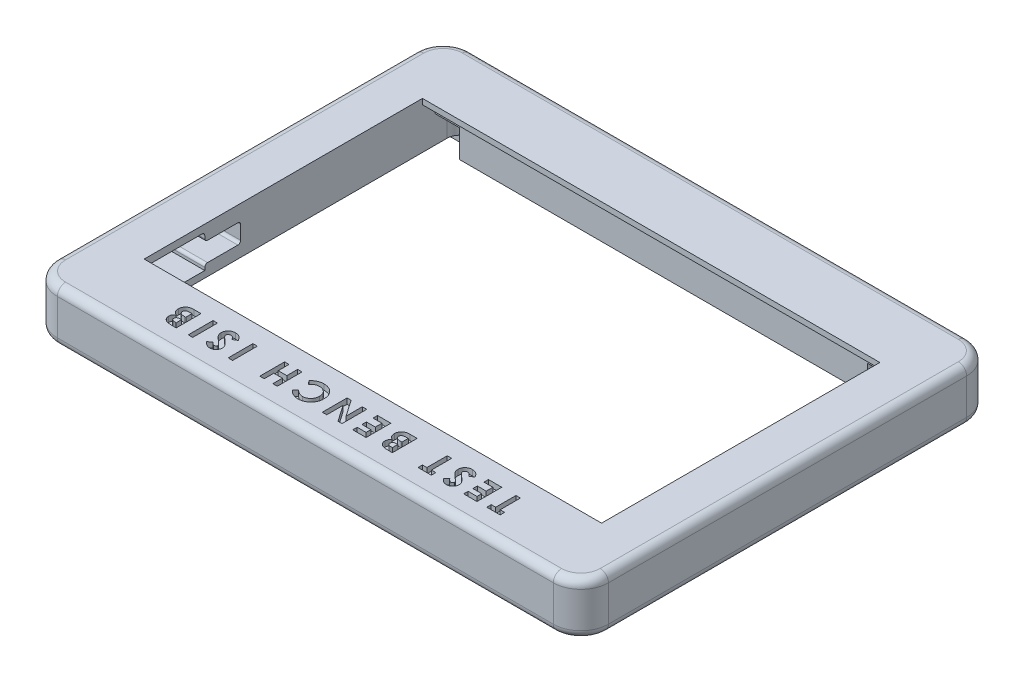
SolidWorks part; units mm, degrees
ref_plane "Plan de face" through (0, 0, 0) normal (0, 0, 1) x (1, 0, 0)
ref_plane "Plan de dessus" through (0, 0, 0) normal (0, 1, 0) x (1, 0, 0)
ref_plane "Plan de droite" through (0, 0, 0) normal (1, 0, 0) x (0, 0, -1)
sketch "Esquisse1" plane through (0, 0, 0) normal (0, 1, 0) x (1, 0, 0)
  line L0 (-100, -75) -> (100, 75) construction
  line L1 (-90, 75) -> (90, 75)
  line L2 (-100, 65) -> (-100, -65)
  line L3 (-90, -75) -> (90, -75)
  line L4 (100, 65) -> (100, -65)
  arc A0 (90, 75) -> (100, 65) centre (90, 65) cw
  arc A1 (90, -75) -> (100, -65) centre (90, -65) ccw
  arc A2 (-90, -75) -> (-100, -65) centre (-90, -65) cw
  arc A3 (-90, 75) -> (-100, 65) centre (-90, 65) ccw
  point P15 (-100, 75)
  dimension "D3" = 10
  dimension "D1" = 200
  dimension "D2" = 150
extrude "Boss.-Extru.1" add sketch "Esquisse1" along normal blind 19
sketch "Esquisse3" plane through (0, 0, 0) normal (0, -1, 0) x (1, 0, 0)
  line L0 (85.1, 62.5) -> (-85.1, -62.5) construction
  line L1 (85.1, -62.5) -> (-85.1, -62.5)
  line L2 (85.1, -62.5) -> (85.1, 62.5)
  line L3 (85.1, 62.5) -> (-85.1, 62.5)
  line L4 (-85.1, -62.5) -> (-85.1, 62.5)
  dimension "D1" = 170.2
  dimension "125" = 125
extrude "Enlèv. mat.-Extru.2" cut sketch "Esquisse3" against normal blind 2
sketch "Esquisse2" plane through (0, 19, 0) normal (0, 1, 0) x (1, 0, 0)
  line L0 (-83, -50.5) -> (83, 50.5) construction
  line L1 (-83, 50.5) -> (83, 50.5)
  line L2 (-83, 50.5) -> (-83, -50.5)
  line L3 (-83, -50.5) -> (83, -50.5)
  line L4 (83, 50.5) -> (83, -50.5)
  dimension "D1" = 166
  dimension "D2" = 101
extrude "Enlèv. mat.-Extru.1" cut sketch "Esquisse2" against normal up to surface (17 mm away) up to face at (0, 2, 0)
sketch "Esquisse4" plane through (0, 2, 0) normal (0, -1, 0) x (1, 0, 0)
  line L0 (-83, 50.5) -> (83, 50.5) construction
  line L6 (-83, -55) -> (-83, -59.5)
  line L17 (-83, -50.5) -> (-83, 50.5) construction
  line L18 (-74, 52.5) -> (74, 52.5)
  line L19 (-83, 52.5) -> (-83, -55)
  line L20 (-74, -55) -> (74, -55)
  line L21 (83, 52.5) -> (83, -55)
  line L22 (-74, -59.5) -> (-74, -55)
  line L23 (83, -55) -> (83, -59.5)
  line L25 (74, -59.5) -> (74, -55)
  line L26 (83, 52.5) -> (83, 57)
  line L28 (74, 57) -> (74, 52.5)
  line L29 (-83, 52.5) -> (-83, 57)
  line L31 (-74, 57) -> (-74, 52.5)
  line L32 (83, 50.5) -> (83, -50.5) construction
  arc A0 (-83, 57) -> (-74, 57) centre (-78.5, 57) cw
  arc A1 (74, 57) -> (83, 57) centre (78.5, 57) cw
  arc A2 (-83, -59.5) -> (-74, -59.5) centre (-78.5, -59.5) ccw
  arc A3 (74, -59.5) -> (83, -59.5) centre (78.5, -59.5) ccw
  dimension "D1" = 2
  dimension "D4" = 4.5
  dimension "D2" = 107.5
  dimension "D3" = 4.5
extrude "Enlèv. mat.-Extru.3" cut sketch "Esquisse4" against normal offset from surface (10 mm away) 7 up to face at (0, 19, 0)
hole_wizard "Trou taraudé M3x0.51" positions "Esquisse5" profile "Esquisse6" tap size "M3x0.5" standard "Ansi Metric"
sketch "Esquisse5" plane through (0, 2, 0) normal (0, -1, 0) x (-1, 0, 0)
  line L1 (-85.1, -62.5) -> (85.1, -62.5) construction
  line L2 (85.1, -62.5) -> (85.1, 62.5) construction
  line L3 (-85.1, 62.5) -> (-85.1, -62.5) construction
  line L4 (85.1, 62.5) -> (81.8541, 62.5) construction
  point P0 (68.1, -59.2)
  point P2 (-68.1, -59.2)
  point P4 (-68.1, 59.2)
  point P6 (68.1, 59.2)
  dimension "D1" = 3.3
  dimension "D2" = 17
  dimension "D3" = 17
  dimension "D4" = 3.3
sketch "Esquisse6" plane through (-68.1, 2, 59.2) normal (1, 0, 0) x (0, 0, -1)
  line L0 (0, 0) -> (0, 11.7511)
  line L1 (0, 11.7511) -> (1.25, 11)
  line L2 (1.25, 11) -> (1.25, 0)
  line L5 (1.25, 0) -> (0, 0)
  line L10 (0, 11.7511) -> (-1.25, 11) construction
  line L11 (0, -6.35) -> (0, 107.95) construction
  dimension "Diamètre du trou pour taraudage" = 2.5
  dimension "Profondeur du trou pour taraudage" = 11
  dimension "Angle de pointe" = 118
cosmetic thread "Filetage de perçage1" parameters "D1"=6, "D2"=3
cosmetic thread "Filetage de perçage2" parameters "D1"=6, "D2"=3
cosmetic thread "Filetage de perçage3" parameters "D1"=6, "D2"=3
cosmetic thread "Filetage de perçage4" parameters "D1"=6, "D2"=3
sketch "Esquisse9" plane through (0, 19, 0) normal (0, 1, 0) x (1, 0, 0)
  line L0 (-70.8312, -57.3182) -> (70.8312, -57.3182) construction
  line L4 (-83, -50.5) -> (83, -50.5) construction
  text T0 "<b>TEST BENCH ISIB</b>" font "Century Gothic" height in points 34
  point P10 (0, -57.3182)
  point P15 (0, -50.5)
extrude "Enlèv. mat.-Extru.5" cut sketch "Esquisse9" against normal blind 2
fillet "Congé1" radius 3 16 edges at (-97.0711, 19, -72.0711) (-97.0711, 19, 72.0711) (-100, 19, 0) (0, 19, -75) (97.0711, 19, -72.0711) (100, 19, 0) (97.0711, 19, 72.0711) (0, 19, 75) (97.0711, 0, 72.0711) (100, 0, 0) (97.0711, 0, -72.0711) (0, 0, -75) (-97.0711, 0, -72.0711) (-100, 0, 0) (0, 0, 75) (-97.0711, 0, 72.0711)
sketch "Esquisse10" plane through (-83, 0, 0) normal (1, 0, 0) x (0, 0, -1)
  line L1 (-47.5, 16.4) -> (-29.5, 16.4)
  line L2 (-50.5, 13.4) -> (-50.5, 7.4)
  line L3 (-47.5, 4.4) -> (-28.5, 4.4)
  line L4 (-15.5, 12.4) -> (-15.5, 7.4)
  line L5 (-24.6694, 10.4) -> (-58.3207, 10.4) construction
  line L6 (-50.5, 12) -> (-57, 12) construction
  line L7 (-28.5, 4.4) -> (-28.5, 5.4)
  line L8 (-27.5, 6.4) -> (-16.5, 6.4)
  line L9 (-16.5, 13.4) -> (-27.5, 13.4)
  line L10 (-28.5, 14.4) -> (-28.5, 15.4)
  line L11 (-50.5, 12) -> (-50.5, 19) construction
  arc A4 (-47.5, 16.4) -> (-50.5, 13.4) centre (-47.5, 13.4) ccw
  arc A5 (-47.5, 4.4) -> (-50.5, 7.4) centre (-47.5, 7.4) cw
  arc A6 (-28.5, 15.4) -> (-29.5, 16.4) centre (-29.5, 15.4) ccw
  arc A7 (-27.5, 13.4) -> (-28.5, 14.4) centre (-27.5, 14.4) cw
  arc A8 (-16.5, 13.4) -> (-15.5, 12.4) centre (-16.5, 12.4) cw
  arc A9 (-15.5, 7.4) -> (-16.5, 6.4) centre (-16.5, 7.4) cw
  arc A10 (-28.5, 5.4) -> (-27.5, 6.4) centre (-27.5, 5.4) cw
  point P1 (-50.5, 10.4)
  point P20 (-15.5, 16.4)
  point P23 (-15.5, 4.4)
  point P26 (-52.5, 19.1935)
  dimension "D4" = 3
  dimension "D7" = 1
  dimension "D1" = 35
  dimension "D2" = 12
  dimension "D3" = 1.6
  dimension "D5" = 22
  dimension "D6" = 7
extrude "Enlèv. mat.-Extru.6" cut sketch "Esquisse10" against normal up to next
sketch "Esquisse11" plane through (0, 12, 0) normal (0, -1, 0) x (1, 0, 0)
  line L0 (-74, -55) -> (-83, -55)
  line L3 (83, -55) -> (74, -55)
  line L6 (83, -50.5) -> (-83, -50.5)
  line L7 (-83, -50.5) -> (-83, -59.5)
  line L8 (-74, -59.5) -> (-74, -55)
  line L9 (-74, -55) -> (74, -55)
  line L10 (74, -55) -> (74, -59.5)
  line L11 (83, -59.5) -> (83, -50.5)
  line L12 (83, -50.5) -> (-83, -50.5)
  line L13 (-83, -50.5) -> (-83, -55)
  line L15 (-74, -55) -> (74, -55)
  line L17 (83, -55) -> (83, -50.5)
  arc A2 (-83, -59.5) -> (-74, -59.5) centre (-78.5, -59.5) ccw
  arc A3 (74, -59.5) -> (83, -59.5) centre (78.5, -59.5) ccw
  dimension "D1" = 0
extrude "Enlèv. mat.-Extru.7" cut sketch "Esquisse11" against normal offset from surface (5 mm away) 2 up to face at (0, 19, 0)
